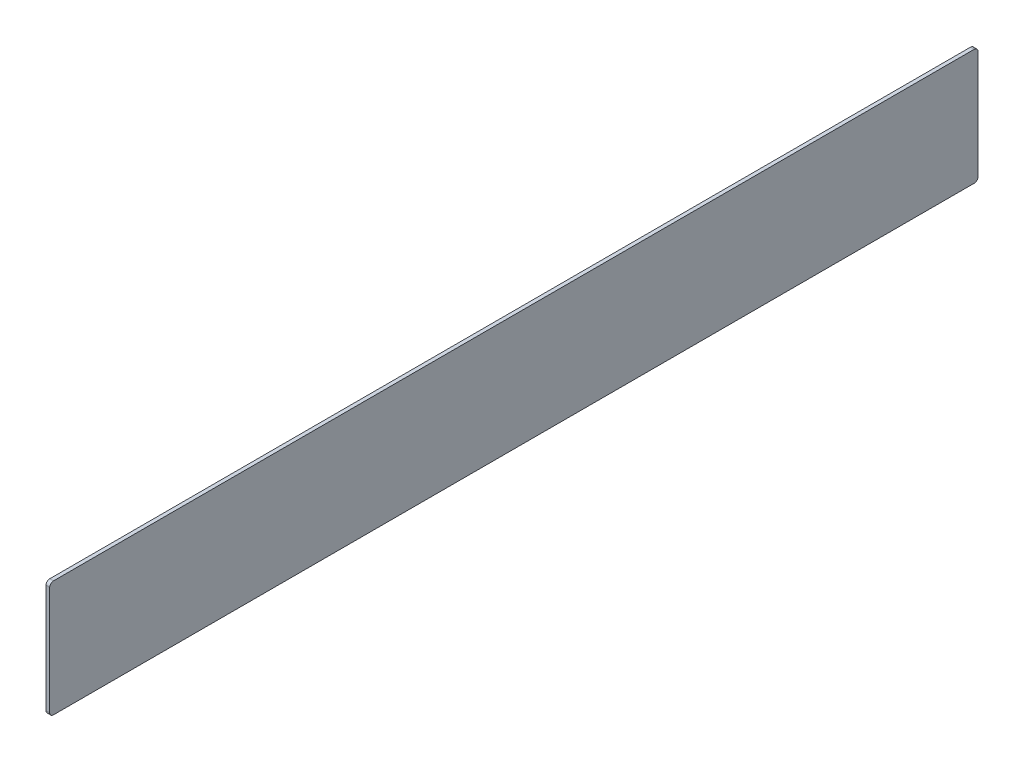
SolidWorks part; units mm, degrees
ref_plane "Front Plane" through (0, 0, 0) normal (0, 0, 1) x (1, 0, 0)
ref_plane "Top Plane" through (0, 0, 0) normal (0, 1, 0) x (1, 0, 0)
ref_plane "Right Plane" through (0, 0, 0) normal (1, 0, 0) x (0, 0, -1)
sketch "Sketch1" plane through (0, 0, 0) normal (1, 0, 0) x (0, 0, -1)
  line L1 (-269.9468, -77.7926) -> (230.0532, -77.7926)
  line L2 (-269.9468, -77.7926) -> (-269.9468, -140.2926)
  line L3 (-269.9468, -140.2926) -> (230.0532, -140.2926)
  line L4 (230.0532, -77.7926) -> (230.0532, -140.2926)
  dimension "D1" = 500
  dimension "D2" = 62.5
extrude "Boss-Extrude1" add sketch "Sketch1" along normal blind 2
fillet "Fillet1" radius 2 4 edges at (1, -140.2926, -230.0532) (1, -77.7926, -230.0532) (1, -140.2926, 269.9468) (1, -77.7926, 269.9468)
